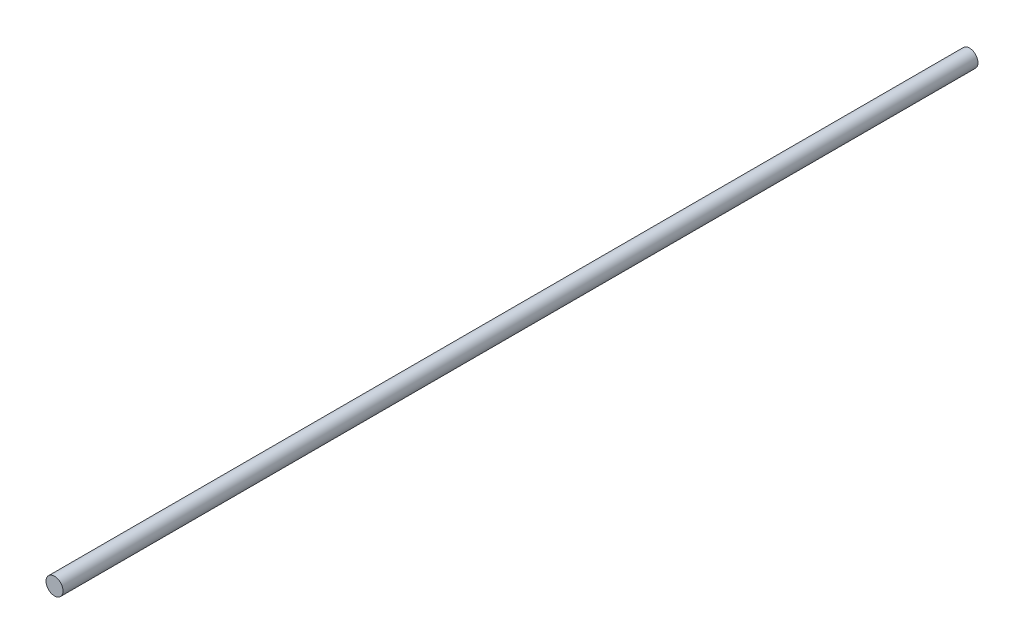
SolidWorks part; units mm, degrees
ref_plane "Front Plane" through (0, 0, 0) normal (0, 0, 1) x (1, 0, 0)
ref_plane "Top Plane" through (0, 0, 0) normal (0, 1, 0) x (1, 0, 0)
ref_plane "Right Plane" through (0, 0, 0) normal (1, 0, 0) x (0, 0, -1)
sketch "Sketch1" plane through (0, 0, 0) normal (0, 0, 1) x (1, 0, 0)
  circle A0 centre (0, 0) radius 3
  circle A1 centre (0, 0) radius 10 construction
  dimension "D1" = 6
  dimension "D2" = 20
extrude "Boss-Extrude1" add sketch "Sketch1" along normal blind 322
